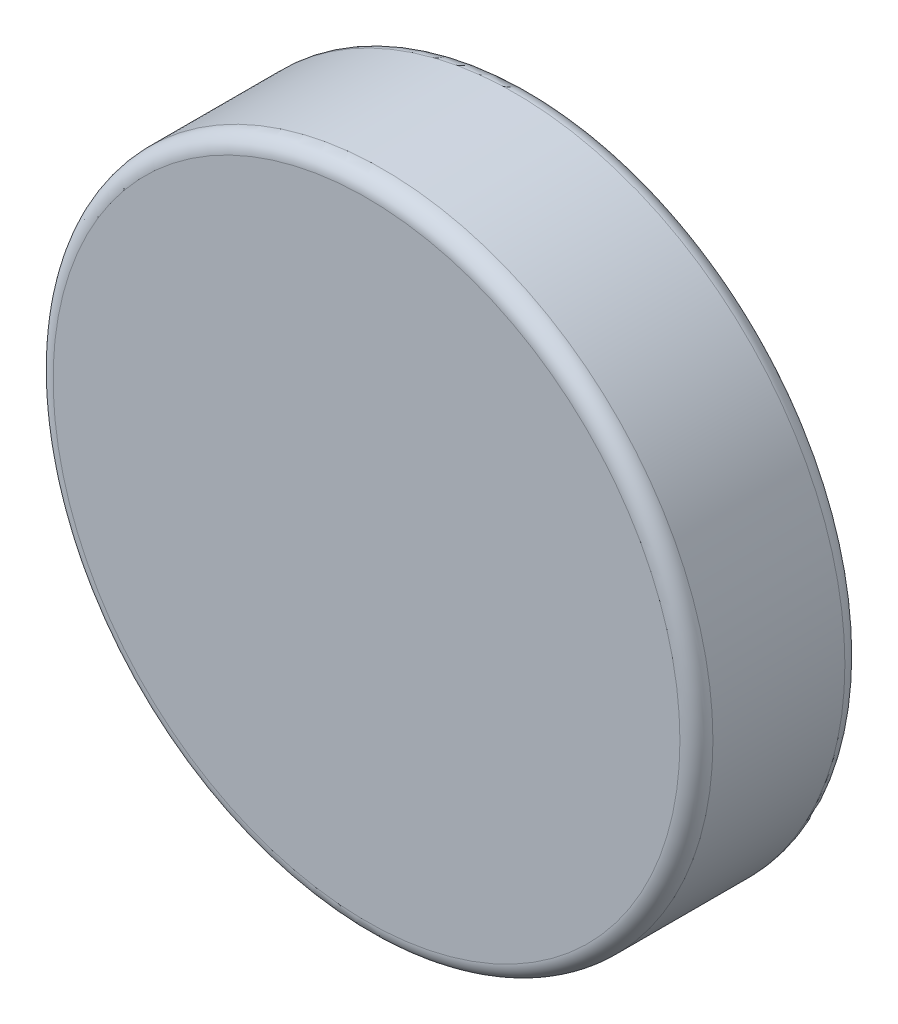
SolidWorks part; units mm, degrees
ref_plane "Top" through (0, 0, 0) normal (0, 0, 1) x (1, 0, 0)
ref_plane "Front" through (0, 0, 0) normal (0, 1, 0) x (1, 0, 0)
ref_plane "Right" through (0, 0, 0) normal (1, 0, 0) x (0, 0, -1)
sketch "Top Sketch" plane through (0, 0, 0) normal (0, 0, 1) x (1, 0, 0)
  circle A0 centre (0, 0) radius 3
  dimension "Diameter" = 6
extrude "Thickness Extrude" add sketch "Top Sketch" along normal blind 1.5
fillet "Edge Fillet" radius 0.15 2 edges at (3, 0, 0) (3, 0, 1.5)
